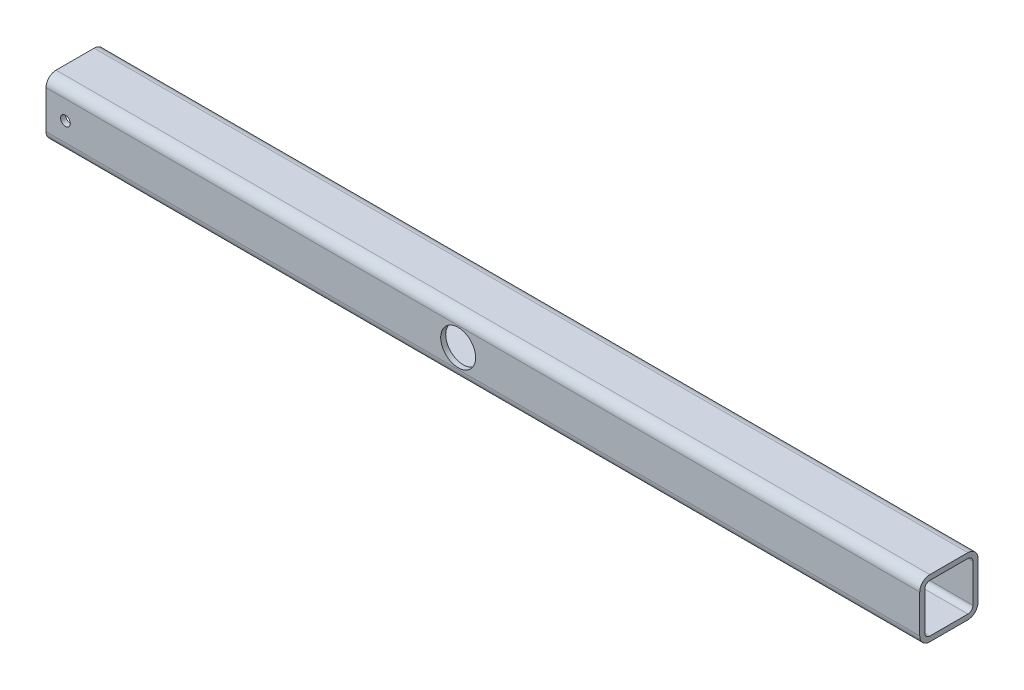
SolidWorks part; units mm, degrees
ref_plane "Płaszczyzna przednia" through (0, 0, 0) normal (0, 0, 1) x (1, 0, 0)
ref_plane "Płaszczyzna górna" through (0, 0, 0) normal (0, 1, 0) x (1, 0, 0)
ref_plane "Płaszczyzna prawa" through (0, 0, 0) normal (1, 0, 0) x (0, 0, -1)
sketch3d "Szkic 3D1"
  line L0 (-225, 0, 0) -> (225, 0, 0)
  dimension "D1" = 450
ref_plane "Płaszczyzna1" through (-225, 0, 0) normal (1, 0, 0) x (0, 0, -1)
other "Rura kwadratowa 30 X 30 X 2.6(1)"
ref_plane "Płaszczyzna2" through (-225, 0, 0) normal (1, 0, 0) x (0, 0, -1)
sketch "Sketch1" plane through (-225, 0, 0) normal (1, 0, 0) x (0, 0, -1)
  line L0 (-9.8, -12.4) -> (9.8, -12.4)
  line L1 (-12.4, -9.8) -> (-12.4, 9.8)
  line L2 (9.8, 12.4) -> (-9.8, 12.4)
  line L3 (12.4, 9.8) -> (12.4, -9.8)
  line L4 (-9.8, -15) -> (9.8, -15)
  line L5 (-15, -9.8) -> (-15, 9.8)
  line L6 (9.8, 15) -> (-9.8, 15)
  line L7 (15, 9.8) -> (15, -9.8)
  arc A0 (15, 9.8) -> (9.8, 15) centre (9.8, 9.8) ccw
  arc A1 (9.8, -15) -> (15, -9.8) centre (9.8, -9.8) ccw
  arc A2 (-15, -9.8) -> (-9.8, -15) centre (-9.8, -9.8) ccw
  arc A3 (-9.8, 15) -> (-15, 9.8) centre (-9.8, 9.8) ccw
  arc A4 (-9.8, 12.4) -> (-12.4, 9.8) centre (-9.8, 9.8) ccw
  arc A5 (12.4, 9.8) -> (9.8, 12.4) centre (9.8, 9.8) ccw
  arc A6 (9.8, -12.4) -> (12.4, -9.8) centre (9.8, -9.8) ccw
  arc A7 (-12.4, -9.8) -> (-9.8, -12.4) centre (-9.8, -9.8) ccw
  point P0 (-15, 0)
  point P1 (15, 0)
  point P2 (0, 15)
  point P3 (0, -15)
  point P4 (0, 0)
  point P5 (-15, -15)
  point P6 (15, -15)
  point P7 (15, 15)
  point P8 (-15, 15)
  point P33 (0, 0)
  dimension "D1" = 5.2
  dimension "Thickness" = 2.6
  dimension "V_leg" = 30
sketch "Szkic2" plane through (0, 0, 15) normal (0, 0, 1) x (1, 0, 0)
  line L0 (-225, 0) -> (225, 0) construction
  line L1 (-225, 9.8) -> (-225, -9.8) construction
  circle A0 centre (-215, 0) radius 2.5
  circle A1 centre (-12.73, 0) radius 9
  dimension "D1" = 5
  dimension "D3" = 18
  dimension "D2" = 10
  dimension "D4" = 202.27
extrude "Wytnij-wyciągnięcie1" cut sketch "Szkic2" against normal through all
